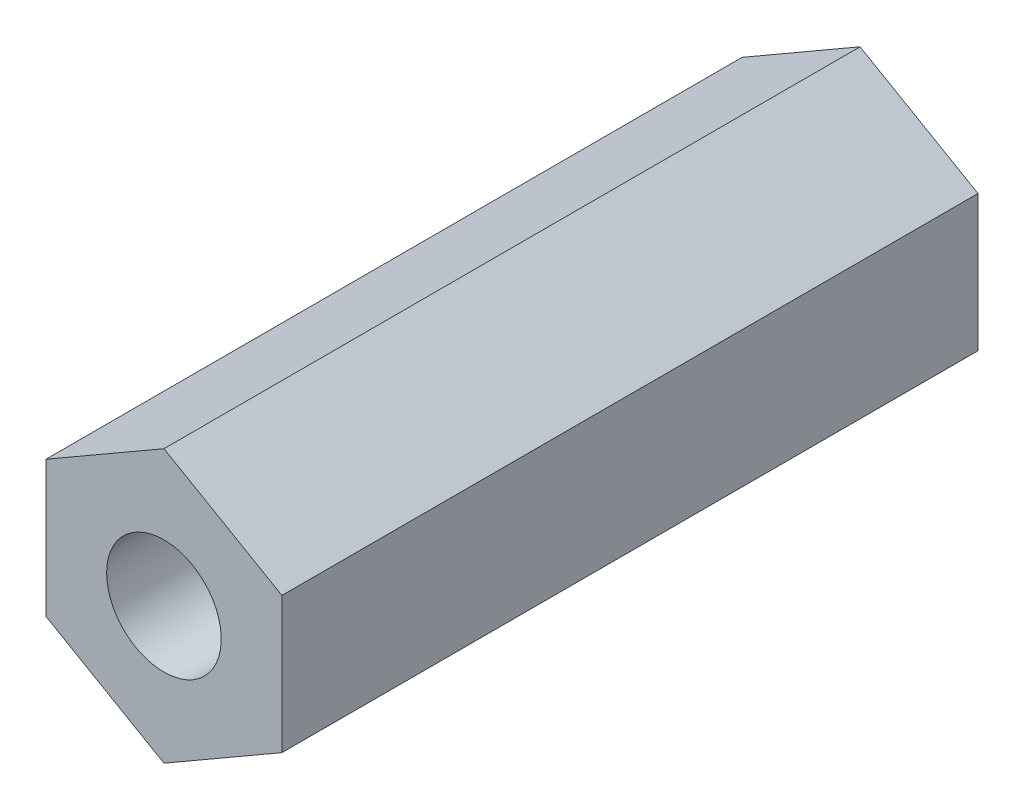
SolidWorks part; units mm, degrees
material "Latón"
ref_plane "Alzado" through (0, 0, 0) normal (0, 0, 1) x (1, 0, 0)
ref_plane "Planta" through (0, 0, 0) normal (0, 1, 0) x (1, 0, 0)
ref_plane "Vista lateral" through (0, 0, 0) normal (1, 0, 0) x (0, 0, -1)
sketch "Croquis1" plane through (0, 0, 0) normal (0, 0, 1) x (1, 0, 0)
  line L0 (39.4987, 38.02) -> (36, 40.04)
  line L1 (36, 40.04) -> (32.5013, 38.02)
  line L2 (32.5013, 38.02) -> (32.5013, 33.98)
  line L3 (32.5013, 33.98) -> (36, 31.96)
  line L4 (36, 31.96) -> (39.4987, 33.98)
  line L5 (39.4987, 33.98) -> (39.4987, 38.02)
  dimension "D1" = 39.4987
  dimension "D2" = 38.02
  dimension "D3" = 36
  dimension "D4" = 40.04
  dimension "D5" = 32.5013
  dimension "D6" = 38.02
  dimension "D7" = 32.5013
  dimension "D8" = 33.98
  dimension "D9" = 36
  dimension "D10" = 31.96
  dimension "D11" = 39.4987
  dimension "D12" = 33.98
extrude "Hex_7" add sketch "Croquis1" along normal blind 20.65 from offset 42.85
sketch "Croquis2" plane through (0, 0, 0) normal (0, 0, 1) x (1, 0, 0)
  circle A0 centre (36, 36) radius 1.7
  dimension "D1" = 3.4
  dimension "D2" = 36
  dimension "D3" = 36
extrude "Rosca_M4" cut sketch "Croquis2" along normal blind 20.65 from offset 42.85
